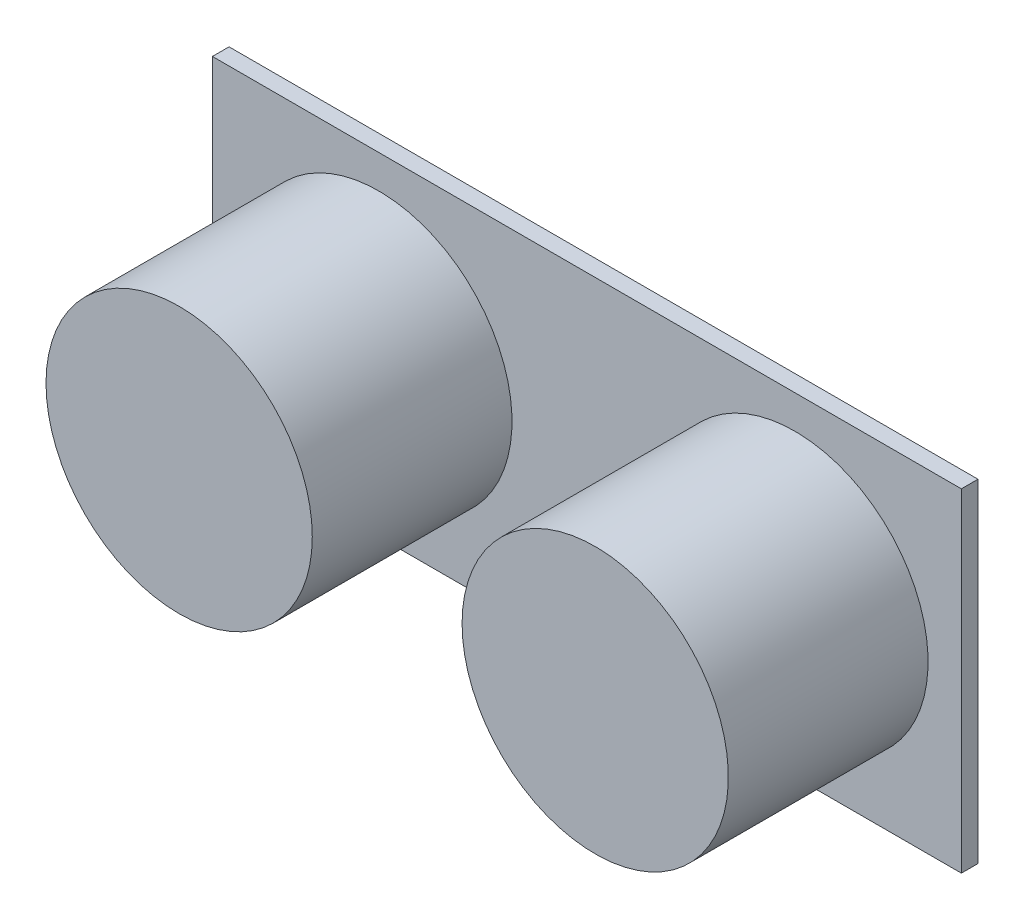
SolidWorks part; units mm, degrees
ref_plane "Front Plane" through (0, 0, 0) normal (0, 0, 1) x (1, 0, 0)
ref_plane "Top Plane" through (0, 0, 0) normal (0, 1, 0) x (1, 0, 0)
ref_plane "Right Plane" through (0, 0, 0) normal (1, 0, 0) x (0, 0, -1)
sketch "Sketch1" plane through (0, 0, 0) normal (0, 0, 1) x (1, 0, 0)
  line L1 (-22.5, -10) -> (22.5, -10)
  line L2 (-22.5, -10) -> (-22.5, 10)
  line L3 (-22.5, 10) -> (22.5, 10)
  line L4 (22.5, -10) -> (22.5, 10)
  line L5 (-22.5, -10) -> (22.5, 10) construction
  line L6 (-22.5, 10) -> (22.5, -10) construction
  point P0 (0, 0)
  dimension "D1" = 20
  dimension "D2" = 45
extrude "Boss-Extrude1" add sketch "Sketch1" along normal blind 1
sketch "Sketch2" plane through (0, 0, 1) normal (0, 0, 1) x (1, 0, 0)
  line L1 (-22.5, 10) -> (-22.5, -10) construction
  circle A0 centre (-12.5, 0) radius 8
  point P2 (-13.537, 1.1297)
  point P3 (0, 0)
  dimension "D1" = 16
  dimension "D3" = 10
extrude "Boss-Extrude2" add sketch "Sketch2" along normal blind 12
mirror "Mirror1" about plane through (0, 0, 0) normal (1, 0, 0) of "Boss-Extrude2"
